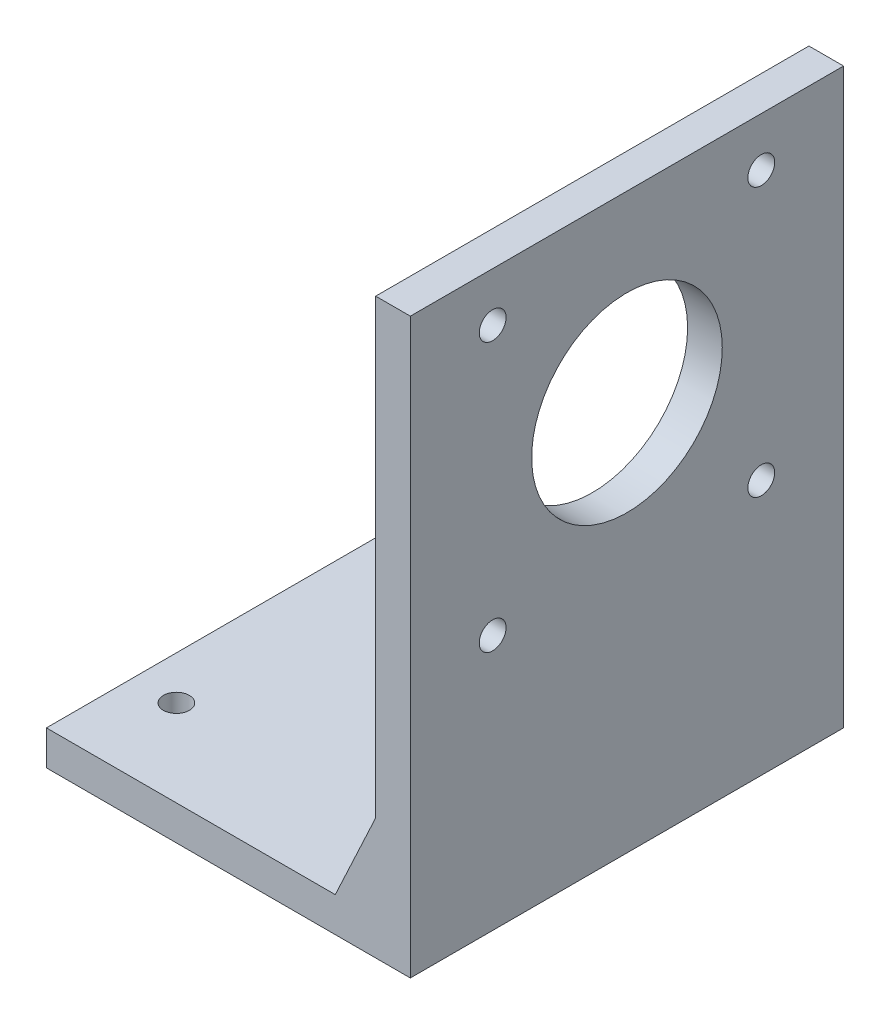
SolidWorks part; units mm, degrees
ref_plane "Front Plane" through (0, 0, 0) normal (0, 0, 1) x (1, 0, 0)
ref_plane "Top Plane" through (0, 0, 0) normal (0, 1, 0) x (1, 0, 0)
ref_plane "Right Plane" through (0, 0, 0) normal (1, 0, 0) x (0, 0, -1)
sketch "Sketch1" plane through (0, 0, 0) normal (1, 0, 0) x (0, 0, -1)
  line L0 (21.15, 33.075) -> (-21.15, -9.225) construction
  line L1 (-25, 33.075) -> (25, 33.075)
  line L2 (-25, 33.075) -> (-25, -33.075)
  line L3 (-25, -33.075) -> (25, -33.075)
  line L4 (25, 33.075) -> (25, -33.075)
  line L5 (0, -33.075) -> (0, 33.075) construction
  line L6 (-25, 0) -> (25, 0) construction
  line L7 (-21.15, 33.075) -> (21.15, 33.075) construction
  line L8 (-21.15, 33.075) -> (-21.15, -9.225) construction
  line L9 (-21.15, -9.225) -> (21.15, -9.225) construction
  line L10 (21.15, 33.075) -> (21.15, -9.225) construction
  line L11 (0, -9.225) -> (0, 33.075) construction
  line L12 (-21.15, 11.925) -> (21.15, 11.925) construction
  line L13 (-21.15, 33.075) -> (21.15, -9.225) construction
  circle A0 centre (0, 11.925) radius 11
  circle A1 centre (-15.5, 27.425) radius 1.55
  circle A2 centre (15.5, 27.425) radius 1.55
  circle A3 centre (15.5, -3.575) radius 1.55
  circle A4 centre (-15.5, -3.575) radius 1.55
  point P0 (0, 0)
  dimension "D3" = 22
  dimension "D6" = 3.1
  dimension "D1" = 50
  dimension "D2" = 45
  dimension "D4" = 42.3
  dimension "D5" = 31
extrude "Boss-Extrude1" add sketch "Sketch1" along normal blind 4
sketch "Sketch2" plane through (0, 0, 0) normal (-1, 0, 0) x (0, 0, 1)
  line L0 (25, 33.075) -> (25, -33.075) construction
  line L1 (-25, -33.075) -> (25, -33.075)
  line L2 (-25, -33.075) -> (-25, -29.075)
  line L3 (-25, -29.075) -> (25, -29.075)
  line L4 (25, -33.075) -> (25, -29.075)
  dimension "D1" = 4
extrude "Boss-Extrude2" add sketch "Sketch2" along normal blind 38
sketch "Sketch3" plane through (0, -29.075, 0) normal (0, 1, 0) x (1, 0, 0)
  line L0 (-23.1, 0) -> (23.1, 0) construction
  line L1 (-38, -25) -> (-38, 25) construction
  circle A0 centre (-33, -15) radius 1.5
  circle A4 centre (-8, -15) radius 1.5
  circle A5 centre (-8, 15) radius 1.5
  circle A6 centre (-33, 15) radius 1.5
  dimension "D1" = 3
  dimension "D2" = 15
  dimension "D3" = 5
  dimension "D4" = 25
extrude "Cut-Extrude1" cut sketch "Sketch3" against normal through all
chamfer "Chamfer1" distance 10 angle 25 1 edges at (0, -29.075, 0)
